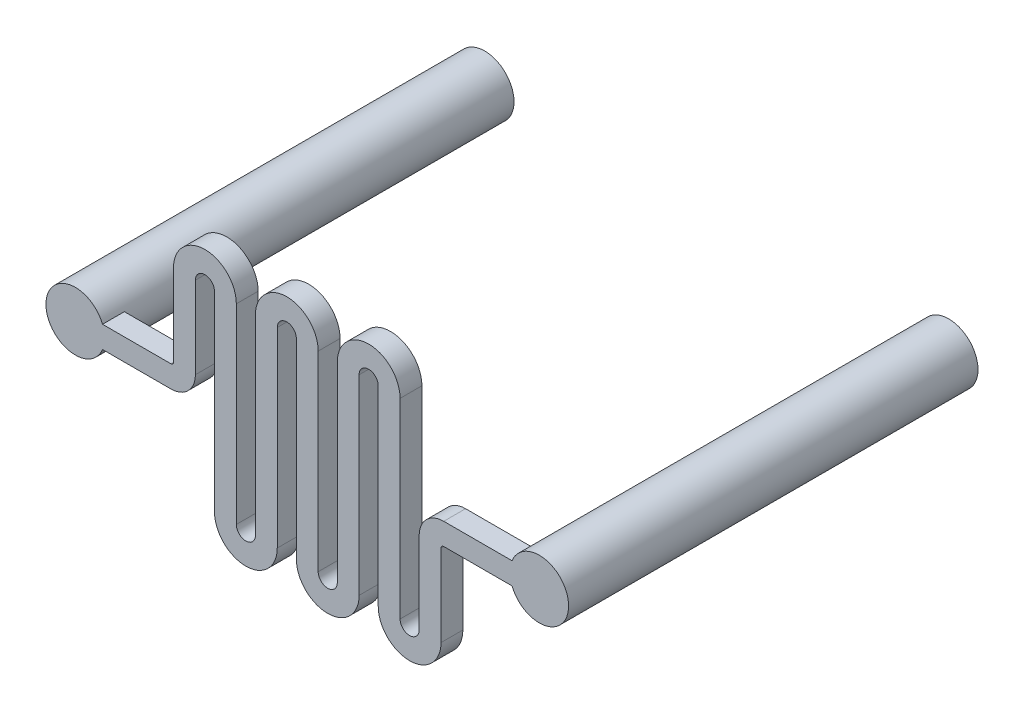
SolidWorks part; units mm, degrees
ref_plane "Front Plane" through (0, 0, 0) normal (0, 0, 1) x (1, 0, 0)
ref_plane "Top Plane" through (0, 0, 0) normal (0, 1, 0) x (1, 0, 0)
ref_plane "Right Plane" through (0, 0, 0) normal (1, 0, 0) x (0, 0, -1)
sketch "Sketch2" plane through (0, 0, 0) normal (0, 0, 1) x (1, 0, 0)
  line L3 (-20.5, -0.8) -> (-13.5, -0.8)
  line L6 (-11.7, 1) -> (-11.7, 7)
  line L9 (-10.3, 7) -> (-10.3, 0)
  line L12 (-10.3, 0) -> (-10.3, -7)
  line L15 (-5.7, -7) -> (-5.7, 0)
  line L18 (-5.7, 0) -> (-5.7, 7)
  line L21 (-4.3, 7) -> (-4.3, 0)
  line L22 (-4.3, 0) -> (-4.3, -7)
  line L23 (0.3, -7) -> (0.3, 0)
  line L24 (0.3, 0) -> (0.3, 7)
  line L25 (1.7, 7) -> (1.7, 0)
  line L26 (1.7, 0) -> (1.7, -7)
  line L27 (6.3, -7) -> (6.3, -1)
  line L28 (6.5, -0.8) -> (13.5, -0.8)
  line L29 (-20.5, 0.8) -> (-13.5, 0.8)
  line L30 (-13.3, 1) -> (-13.3, 7)
  line L31 (-8.7, 7) -> (-8.7, 0)
  line L32 (-8.7, 0) -> (-8.7, -7)
  line L33 (-7.3, -7) -> (-7.3, 0)
  line L34 (-7.3, 0) -> (-7.3, 7)
  line L35 (-2.7, 7) -> (-2.7, 0)
  line L36 (-2.7, 0) -> (-2.7, -7)
  line L37 (-1.3, -7) -> (-1.3, 0)
  line L38 (-1.3, 0) -> (-1.3, 7)
  line L39 (3.3, 7) -> (3.3, 0)
  line L40 (3.3, 0) -> (3.3, -7)
  line L41 (4.7, -7) -> (4.7, -1)
  line L42 (6.5, 0.8) -> (13.5, 0.8)
  arc A8 (-11.7, 1) -> (-13.5, -0.8) centre (-13.5, 1) cw
  arc A9 (-11.7, 7) -> (-10.3, 7) centre (-11, 7) cw
  arc A10 (-10.3, -7) -> (-5.7, -7) centre (-8, -7) ccw
  arc A11 (-5.7, 7) -> (-4.3, 7) centre (-5, 7) cw
  arc A12 (-4.3, -7) -> (0.3, -7) centre (-2, -7) ccw
  arc A13 (0.3, 7) -> (1.7, 7) centre (1, 7) cw
  arc A14 (1.7, -7) -> (6.3, -7) centre (4, -7) ccw
  arc A15 (6.3, -1) -> (6.5, -0.8) centre (6.5, -1) cw
  arc A16 (-13.3, 1) -> (-13.5, 0.8) centre (-13.5, 1) cw
  arc A17 (-13.3, 7) -> (-8.7, 7) centre (-11, 7) cw
  arc A18 (-8.7, -7) -> (-7.3, -7) centre (-8, -7) ccw
  arc A19 (-7.3, 7) -> (-2.7, 7) centre (-5, 7) cw
  arc A20 (-2.7, -7) -> (-1.3, -7) centre (-2, -7) ccw
  arc A21 (-1.3, 7) -> (3.3, 7) centre (1, 7) cw
  arc A22 (3.3, -7) -> (4.7, -7) centre (4, -7) ccw
  arc A23 (4.7, -1) -> (6.5, 0.8) centre (6.5, -1) cw
  arc A24 (-20.5, 0.8) -> (-20.5, -0.8) centre (-20.5, 0) ccw
  arc A25 (13.5, -0.8) -> (13.5, 0.8) centre (13.5, 0) ccw
  point P4 (0, 0)
  point P32 (5.5, 0)
  point P35 (-12.5, 0)
  dimension "D1" = 8
  dimension "D14" = 8
extrude "Boss-Extrude1" add sketch "Sketch2" along normal blind 1.6
ref_plane "Plane1" through (0, 0, 0) normal (0, 1, 0) x (1, 0, 0)
ref_plane "Plane2" through (0, 0, 0) normal (0, 1, 0) x (1, 0, 0)
sketch "Sketch3" plane through (0, 0, 0) normal (0, 1, 0) x (1, 0, 0)
  line L1 (-20.5, 28.4) -> (-22.65, 28.4)
  line L2 (-20.5, -1.6) -> (-20.5, 28.4)
  line L6 (-22.65, 28.4) -> (-22.65, -1.6)
  line L7 (-22.65, -1.6) -> (-20.5, -1.6)
  dimension "D1" = 30
  dimension "D2" = 2.15
sketch "Sketch4" plane through (0, 0, 0) normal (0, 1, 0) x (1, 0, 0)
  line L1 (13.5, 28.4) -> (15.65, 28.4)
  line L2 (13.5, -1.6) -> (13.5, 28.4)
  line L6 (15.65, 28.4) -> (15.65, -1.6)
  line L7 (15.65, -1.6) -> (13.5, -1.6)
  dimension "D1" = 2.15
  dimension "D3" = 30
revolve "Revolve1" add sketch "Sketch3" angle 360 about L2
revolve "Revolve2" add sketch "Sketch4" angle 360 about L2
sketch "Sketch5" plane through (0, 0, -28.4) normal (0, 0, -1) x (-1, 0, 0)
  circle A0 centre (20.5, 0) radius 1.5
  circle A1 centre (-13.5, 0) radius 1.5
  dimension "D1" = 3
  dimension "D2" = 3
extrude "Cut-Extrude1" cut sketch "Sketch5" against normal blind 28
